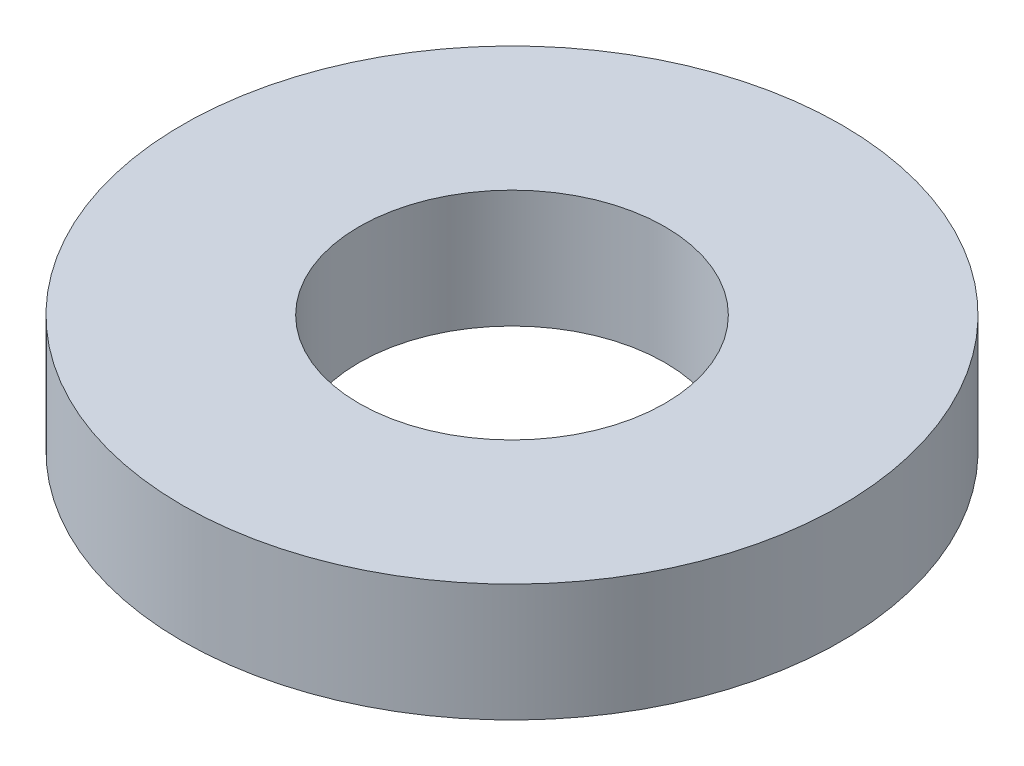
SolidWorks part; units mm, degrees
ref_plane "Plan de face" through (0, 0, 0) normal (0, 0, 1) x (1, 0, 0)
ref_plane "Plan de dessus" through (0, 0, 0) normal (0, 1, 0) x (1, 0, 0)
ref_plane "Plan de droite" through (0, 0, 0) normal (1, 0, 0) x (0, 0, -1)
sketch "Esquisse1" plane through (0, 0, 0) normal (0, 1, 0) x (1, 0, 0)
  circle A0 centre (0, 0) radius 2.6
  circle A1 centre (0, 0) radius 5.6
  dimension "D1" = 5.2
  dimension "D2" = 3
extrude "Boss.-Extru.1" add sketch "Esquisse1" along normal blind 2
